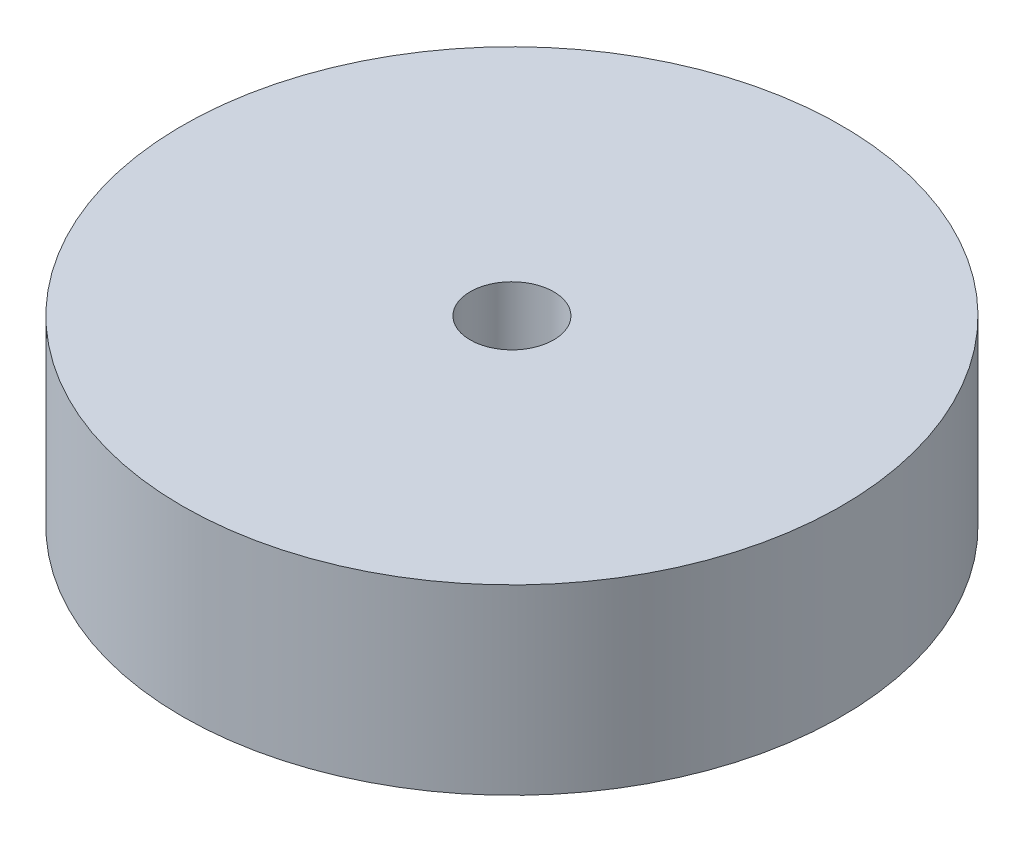
SolidWorks part; units mm, degrees
ref_plane "Front Plane" through (0, 0, 0) normal (0, 0, 1) x (1, 0, 0)
ref_plane "Top Plane" through (0, 0, 0) normal (0, 1, 0) x (1, 0, 0)
ref_plane "Right Plane" through (0, 0, 0) normal (1, 0, 0) x (0, 0, -1)
sketch "Sketch1" plane through (0, 0, 0) normal (0, 1, 0) x (1, 0, 0)
  circle A0 centre (0, 0) radius 1.375
  circle A1 centre (0, 0) radius 10.85
  dimension "D1" = 21.7
  dimension "D2" = 2.75
extrude "Boss-Extrude1" add sketch "Sketch1" along normal blind 6
